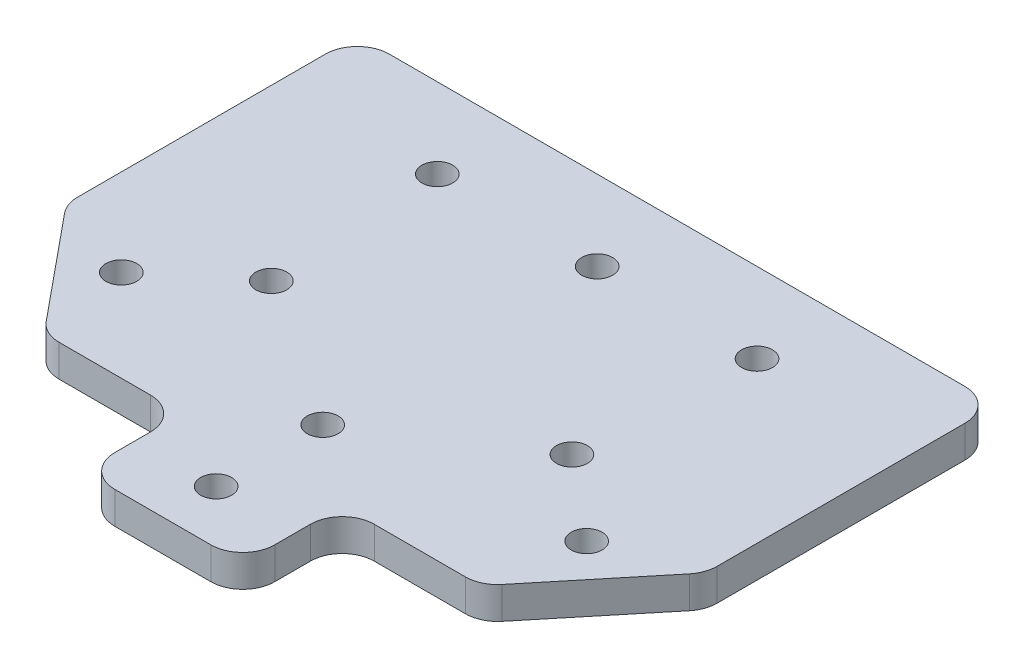
SolidWorks part; units mm, degrees
material "Thornel Mat VMA"
ref_plane "前视基准面" through (0, 0, 0) normal (0, 0, 1) x (1, 0, 0)
ref_plane "上视基准面" through (0, 0, 0) normal (0, 1, 0) x (1, 0, 0)
ref_plane "右视基准面" through (0, 0, 0) normal (1, 0, 0) x (0, 0, -1)
other "Configuration Table"
sketch "草图1" plane through (0, 0, 0) normal (0, 1, 0) x (1, 0, 0)
  line L0 (-15, 150) -> (-185, 10.3576) construction
  line L1 (-185, -150) -> (185, -150) construction
  line L2 (-185, -150) -> (-185, 150) construction
  line L3 (-185, 150) -> (185, 150) construction
  line L4 (185, -150) -> (185, 150) construction
  line L5 (-185, -150) -> (185, 150) construction
  line L6 (-185, 150) -> (185, -150) construction
  line L7 (-15, 150) -> (-5.4789, 138.4091) construction
  line L8 (-185, 10.3576) -> (-175.4789, -1.2333) construction
  line L9 (-5.4789, 138.4091) -> (-175.4789, -1.2333) construction
  line L10 (0, 196.6631) -> (0, -186.1301) construction
  line L11 (185, 10.3576) -> (175.4789, -1.2333) construction
  line L12 (15, 150) -> (5.4789, 138.4091) construction
  line L13 (5.4789, 138.4091) -> (175.4789, -1.2333) construction
  line L14 (15, 150) -> (185, 10.3576) construction
  line L15 (185, 150) -> (200, 150) construction
  line L16 (-185, 150) -> (185, 150) construction
  line L17 (-185, 150) -> (-185, 165) construction
  line L18 (-185, 165) -> (185, 165) construction
  line L19 (185, 150) -> (185, 165) construction
  line L20 (-185, 150) -> (-200, 150) construction
  line L21 (-185, 150) -> (-185, -150) construction
  line L22 (-185, -150) -> (-200, -150) construction
  line L23 (-200, 150) -> (-200, -150) construction
  line L24 (185, -150) -> (200, -150) construction
  line L25 (200, 150) -> (200, -150) construction
  line L26 (-200, -33) -> (-185, -33) construction
  line L27 (-30, 165) -> (-30, 118.2668) construction
  line L28 (-30, 118.2668) -> (30, 118.2668) construction
  line L29 (30, 118.2668) -> (30, 165) construction
  line L30 (30, 165) -> (-30, 165)
  line L31 (-47.9147, 157.5) -> (59.658, 157.5) construction
  line L32 (-14.1031, 141.0309) -> (-21.8304, 134.6835) construction
  line L33 (-30, 165) -> (-30, 137.6786)
  line L34 (-30, 137.6786) -> (-20.4789, 126.0877)
  line L35 (-20.4789, 126.0877) -> (20.4789, 126.0877) construction
  line L36 (20.4789, 126.0877) -> (30, 137.6786)
  line L37 (30, 137.6786) -> (30, 165)
  line L38 (-14.392, 131.0877) -> (0, 142.9096) construction
  line L39 (0, 142.9096) -> (14.392, 131.0877) construction
  line L40 (14.392, 131.0877) -> (-14.392, 131.0877) construction
  line L41 (-7.5, 136.7489) -> (7.5, 136.7489) construction
  line L42 (-7.5, 136.7489) -> (-7.5, 89.35) construction
  line L43 (7.5, 136.7489) -> (7.5, 88.3022) construction
  line L44 (-20.4789, 126.0877) -> (-7.5, 126.0877)
  line L45 (-7.5, 126.0877) -> (-7.5, 116.7489)
  line L46 (-7.5, 116.7489) -> (7.5, 116.7489)
  line L47 (7.5, 116.7489) -> (7.5, 126.0877)
  line L48 (7.5, 126.0877) -> (20.4789, 126.0877)
  circle A0 centre (0, 157.5) radius 1.45
  circle A1 centre (-15, 157.5) radius 1.45
  circle A2 centre (-14.1031, 141.0309) radius 1.45
  circle A3 centre (-21.8304, 134.6835) radius 1.45
  circle A4 centre (21.8304, 134.6835) radius 1.45
  circle A5 centre (14.1031, 141.0309) radius 1.45
  circle A6 centre (15, 157.5) radius 1.45
  circle A7 centre (0, 131.7489) radius 1.45
  circle A8 centre (0, 121.7489) radius 1.45
  point P0 (0, 0)
  dimension "D9" = 2.9
  dimension "D10" = 5
  dimension "D11" = 10
  dimension "D12" = 15
  dimension "D18" = 5
  dimension "D19" = 10
  dimension "D20" = 5
  dimension "D1" = 370
  dimension "D2" = 300
  dimension "D3" = 220
  dimension "D4" = 15
  dimension "D5" = 15
  dimension "D6" = 183
  dimension "D7" = 170
  dimension "D8" = 15
  dimension "D13" = 15
  dimension "D14" = 7.5
  dimension "D15" = 7.5
  dimension "D16" = 5
  dimension "D17" = 15
extrude "凸台-拉伸1" add sketch "草图1" along normal blind 3
fillet "圆角1" radius 3 10 edges at (30, 1.5, -137.6786) (-30, 1.5, -137.6786) (-30, 1.5, -165) (30, 1.5, -165) (20.4789, 1.5, -126.0877) (7.5, 1.5, -126.0877) (7.5, 1.5, -116.7489) (-7.5, 1.5, -116.7489) (-20.4789, 1.5, -126.0877) (-7.5, 1.5, -126.0877)
